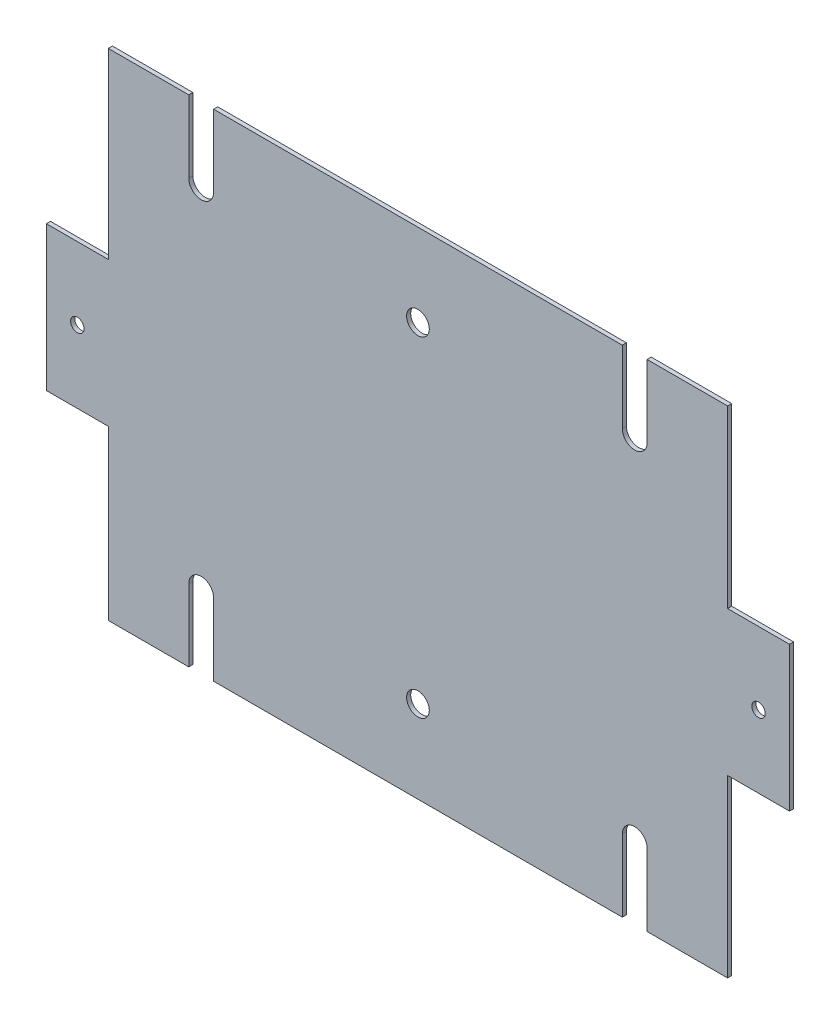
SolidWorks part; units mm, degrees
material "Galvanized Steel"
ref_plane "Front Plane" through (0, 0, 0) normal (0, 0, 1) x (1, 0, 0)
ref_plane "Top Plane" through (0, 0, 0) normal (0, 1, 0) x (1, 0, 0)
ref_plane "Right Plane" through (0, 0, 0) normal (1, 0, 0) x (0, 0, -1)
sketch "Sketch1" plane through (0, 0, 0) normal (0, 0, 1) x (1, 0, 0)
  line L0 (68.9488, -26.6338) -> (98.9488, -26.6338)
  line L1 (68.9488, 58.3662) -> (29.9488, 58.3662)
  line L2 (68.9488, 58.3662) -> (68.9488, -26.6338)
  line L3 (68.9488, -181.6338) -> (29.9488, -181.6338)
  line L4 (-231.0512, 58.3662) -> (-231.0512, -30.1799)
  line L5 (98.9488, -26.6338) -> (98.9488, -96.6338)
  line L6 (98.9488, -96.6338) -> (68.9488, -96.6338)
  line L7 (-231.0512, -30.1799) -> (-261.0512, -30.1799)
  line L8 (-261.0512, -30.1799) -> (-261.0512, -100.1799)
  line L9 (-261.0512, -100.1799) -> (-231.0512, -100.1799)
  line L10 (-231.0512, -100.1799) -> (-231.0512, -181.6338)
  line L11 (68.9488, -96.6338) -> (68.9488, -181.6338)
  line L12 (17.9488, -181.6338) -> (-180.0512, -181.6338)
  line L13 (-180.0512, 58.3662) -> (-180.0512, 23.3662)
  line L14 (-192.0512, 58.3662) -> (-192.0512, 23.3662)
  line L16 (-192.0512, -181.6338) -> (-192.0512, -146.6338)
  line L17 (-180.0512, -181.6338) -> (-180.0512, -146.6338)
  line L18 (-192.0512, -181.6338) -> (-231.0512, -181.6338)
  line L19 (29.9488, -146.6338) -> (29.9488, -181.6338)
  line L20 (17.9488, -146.6338) -> (17.9488, -181.6338)
  line L21 (-192.0512, 58.3662) -> (-231.0512, 58.3662)
  line L22 (29.9488, 58.3662) -> (29.9488, 23.3662)
  line L23 (17.9488, 58.3662) -> (17.9488, 23.3662)
  line L24 (17.9488, 58.3662) -> (-180.0512, 58.3662)
  circle A0 centre (-81.0512, -141.6338) radius 5.5
  arc A1 (-192.0512, 23.3662) -> (-180.0512, 23.3662) centre (-186.0512, 23.3662) ccw
  circle A2 centre (-81.0512, 18.3662) radius 5.5
  arc A3 (-180.0512, -146.6338) -> (-192.0512, -146.6338) centre (-186.0512, -146.6338) ccw
  arc A4 (29.9488, -146.6338) -> (17.9488, -146.6338) centre (23.9488, -146.6338) ccw
  circle A5 centre (83.9488, -61.6338) radius 3.25
  circle A6 centre (-246.0512, -65.1799) radius 3.25
  arc A7 (17.9488, 23.3662) -> (29.9488, 23.3662) centre (23.9488, 23.3662) ccw
  point P14 (-186.0512, 50.7838)
  point P21 (-186.0512, -182.4408)
  point P26 (23.9488, -182.4408)
  point P33 (23.9488, 50.7838)
  dimension "D18" = 11
  dimension "D19" = 11
  dimension "D20" = 6.5
  dimension "D21" = 6.5
  dimension "D26" = 11
  dimension "D27" = 6.5
  dimension "D1" = 240
  dimension "D2" = 300
  dimension "D3" = 30
  dimension "D4" = 70
  dimension "D5" = 45
  dimension "D6" = 30
  dimension "D7" = 70
  dimension "D8" = 12
  dimension "D9" = 12
  dimension "D10" = 39
  dimension "D11" = 39
  dimension "D12" = 12
  dimension "D13" = 12
  dimension "D14" = 35
  dimension "D15" = 35
  dimension "D16" = 35
  dimension "D17" = 35
  dimension "D22" = 150
  dimension "D23" = 40
  dimension "D24" = 150
  dimension "D25" = 40
  dimension "D28" = 15
  dimension "D29" = 35
  dimension "D30" = 15
  dimension "D31" = 35
extrude "Boss-Extrude1" add sketch "Sketch1" along normal blind 2
